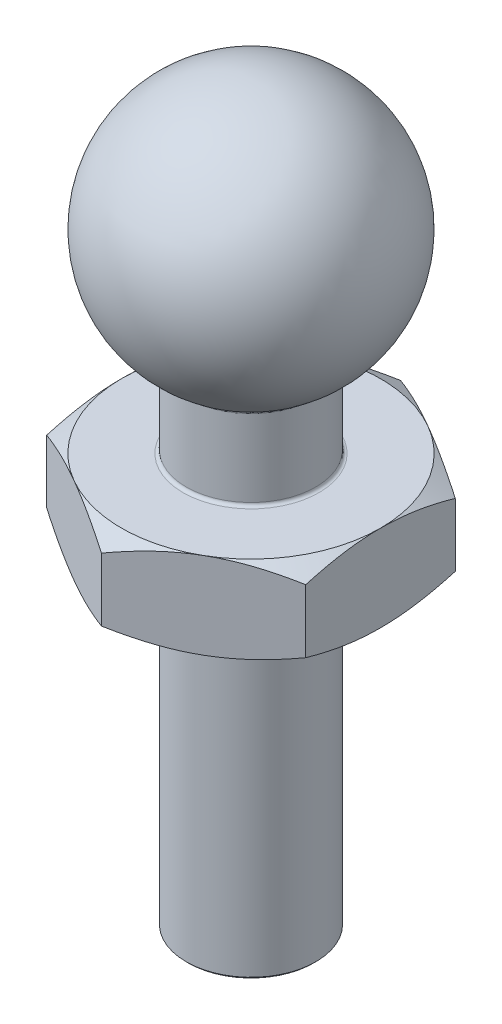
SolidWorks part; units mm, degrees
ref_plane "Front Plane" through (0, 0, 0) normal (0, 0, 1) x (1, 0, 0)
ref_plane "Top Plane" through (0, 0, 0) normal (0, 1, 0) x (1, 0, 0)
ref_plane "Right Plane" through (0, 0, 0) normal (1, 0, 0) x (0, 0, -1)
sketch "Sketch1" plane through (0, 0, 0) normal (0, 0, 1) x (1, 0, 0)
  line L0 (0, 17) -> (0, 0)
  line L1 (1.5, 11.4019) -> (1.5, 0)
  line L2 (1.5, 0) -> (0, 0)
  circle A0 centre (0, 14) radius 3 construction
  arc A2 (1.5, 11.4019) -> (0, 17) centre (0, 14) ccw
  dimension "D1" = 6
  dimension "D2" = 14
  dimension "D3" = 1.5
revolve "Revolve1" add sketch "Sketch1" angle 360 about L0
sketch "Sketch2" plane through (0, 0, 0) normal (0, 0, 1) x (1, 0, 0)
  line L0 (-4.6762, 7.5) -> (4.6762, 7.5)
  point P2 (0, 7.5)
  dimension "D1" = 9.3524
  dimension "D2" = 7.5
split line "Split Line1"
chamfer "Chamfer1" distance 0.05 angle 45 1 edges at (0, 0, 1.5)
ref_plane "Plane1" through (0, 7.5, 0) normal (0, 1, 0) x (1, 0, 0)
sketch "Sketch3" plane through (0, 7.5, 0) normal (0, 1, 0) x (1, 0, 0)
  line L1 (3, 1.7321) -> (0, 3.4641)
  line L2 (0, 3.4641) -> (-3, 1.7321)
  line L3 (-3, 1.7321) -> (-3, -1.7321)
  line L4 (-3, -1.7321) -> (0, -3.4641)
  line L5 (0, -3.4641) -> (3, -1.7321)
  line L6 (3, -1.7321) -> (3, 1.7321)
  circle A0 centre (0, 0) radius 1.5
  circle A1 centre (0, 0) radius 3 construction
  circle A2 centre (0, 0) radius 1.5 construction
  point P3 (0, 0)
  dimension "D1" = 6
extrude "Boss-Extrude1" add sketch "Sketch3" along normal blind 2
sketch "Sketch5" plane through (0, 7.5, 0) normal (0, -1, 0) x (1, 0, 0)
  circle A0 centre (0, 0) radius 3 construction
  circle A1 centre (0, 0) radius 3
extrude "Cut-Extrude1" cut sketch "Sketch5" against normal blind 2 draft 60 flip side to cut
ref_plane "Plane2" through (0, 8.5, 0) normal (0, -1, 0) x (-1, 0, 0)
mirror "Mirror1" about plane through (0, 8.5, 0) normal (0, -1, 0) of "Cut-Extrude1"
fillet "Fillet1" radius 0.075 2 edges at (0, 11.4019, 1.5) (0, 9.5, 1.5)
